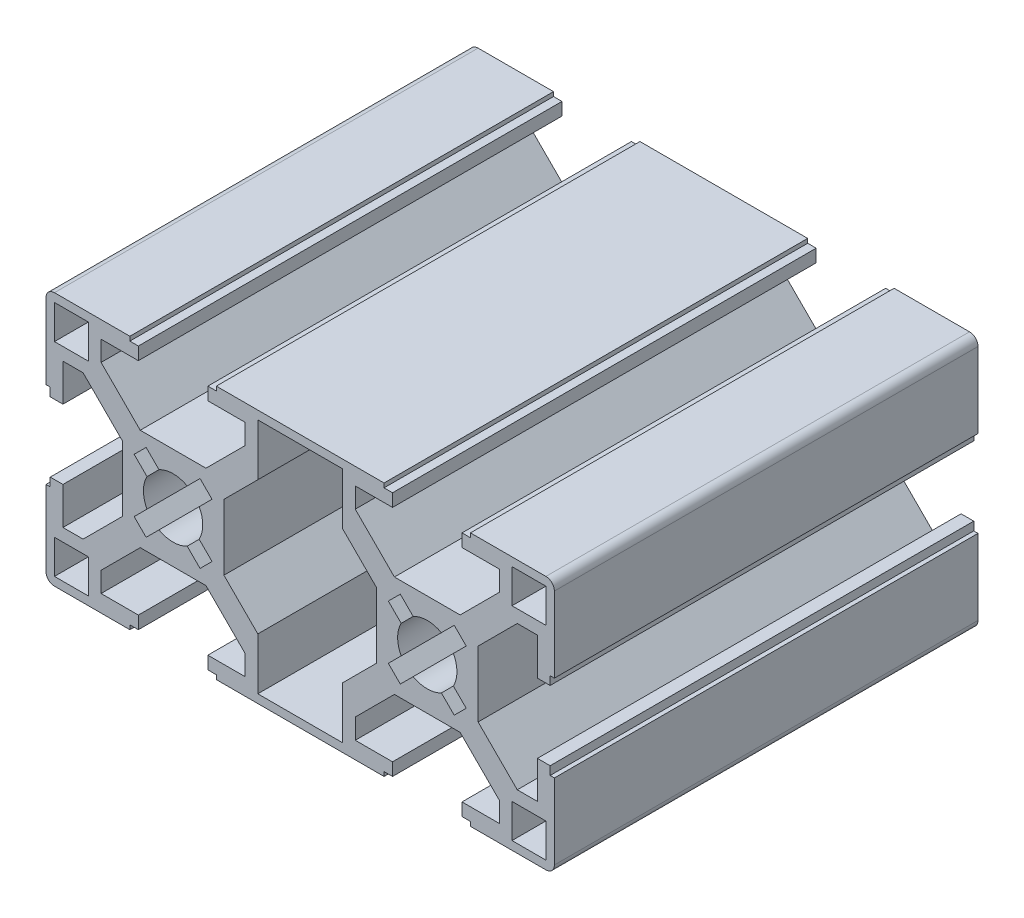
SolidWorks part; units mm, degrees
material "6063-T83"
ref_plane "Plano frontal" through (0, 0, 0) normal (0, 0, 1) x (1, 0, 0)
ref_plane "Plano superior" through (0, 0, 0) normal (0, 1, 0) x (1, 0, 0)
ref_plane "Plano direito" through (0, 0, 0) normal (1, 0, 0) x (0, 0, -1)
sketch "Esboço1" plane through (0, 0, 0) normal (0, 0, 1) x (1, 0, 0)
  line L5 (0, 0) -> (-17.7944, 17.7944) construction
  line L6 (0, 3.5) -> (0, 6)
  line L8 (0, 6) -> (-3.8787, 6)
  line L9 (-3.5, 0) -> (-6, 0)
  line L48 (-6, 0) -> (-6, 3.8787)
  line L49 (-3.8787, 6) -> (-8.5, 10.6213)
  line L50 (-6, 3.8787) -> (-10.6213, 8.5)
  line L51 (0, 0) -> (-12.921, 0) construction
  line L52 (-8.5, 13) -> (-4.1, 13)
  line L53 (-4.1, 13) -> (-4.1, 14.5)
  line L54 (-4.1, 14.5) -> (-5.1, 14.5)
  line L55 (-5.1, 14.5) -> (-5.1, 15)
  line L56 (-5.1, 15) -> (-15, 15)
  line L57 (-15, 5.1) -> (-15, 15)
  line L58 (-14.5, 5.1) -> (-15, 5.1)
  line L59 (-14.5, 4.1) -> (-14.5, 5.1)
  line L60 (-13, 4.1) -> (-14.5, 4.1)
  line L61 (-13, 8.5) -> (-13, 4.1)
  line L62 (-1.6646, 3.0788) -> (-3.182, 4.5962)
  line L63 (-3.0788, 1.6646) -> (-4.5962, 3.182)
  line L64 (-4.5962, 3.182) -> (-3.182, 4.5962)
  line L65 (-8.5, 13) -> (-8.5, 10.6213)
  line L66 (-10, 14) -> (-14, 14)
  line L67 (-10, 14) -> (-10, 10)
  line L68 (-10, 10) -> (-14, 10)
  line L69 (-14, 14) -> (-14, 10)
  line L70 (-10, 14) -> (-14, 10) construction
  line L71 (-10, 10) -> (-14, 14) construction
  line L72 (-13, 8.5) -> (-10.6213, 8.5)
  circle A1 centre (0, 0) radius 3.5
  point P25 (-12, 12)
  dimension "D5" = 10.9
  dimension "D9" = 5.5
  dimension "D10" = 2
  dimension "D11" = 4
  dimension "D12" = 4
  dimension "D13" = 1
  dimension "D1" = 7
  dimension "D2" = 6
  dimension "D3" = 3
  dimension "D4" = 9.9
  dimension "D6" = 0.5
  dimension "D7" = 1.5
  dimension "D8" = 15
  dimension "D14" = 6.5
extrude "Ressalto-extrusão1" add sketch "Esboço1" along normal blind 50 contours A1 L6 L8 L49 L65 L52 L53 L54 L55 L56 L57 L58 L59 L60 L61 L72 L50 L48 L9 L63 L64 L62 L69 L66 L67 L68
sketch "Esboço3" plane through (0, 0, 0) normal (1, 0, 0) x (0, 0, -1)
  line L0 (0, 0) -> (-1000, 0) construction
  dimension "D1" = 1000
pattern_circular "PadrãoCircular1" count 4 every 90 about axis through (0, 0, 0) along (0, 0, 1) of "Ressalto-extrusão1"
pattern_linear "Padrão linear1" count 2 spacing 30 along (1, 0, 0) of "Ressalto-extrusão1", "PadrãoCircular1"
sketch "Esboço4" plane through (0, 0, 0) normal (0, 0, -1) x (-1, 0, 0)
  line L0 (-20, 14) -> (-20, -14)
  line L1 (-20, -14) -> (-10, -14)
  line L2 (-10, -14) -> (-10, 14)
  line L3 (-10, 14) -> (-20, 14)
extrude "Corte-extrusão1" cut sketch "Esboço4" against normal through all
fillet "Filete1" radius 1 4 edges at (45, -15, 25) (45, 15, 25) (-15, 15, 25) (-15, -15, 25)
